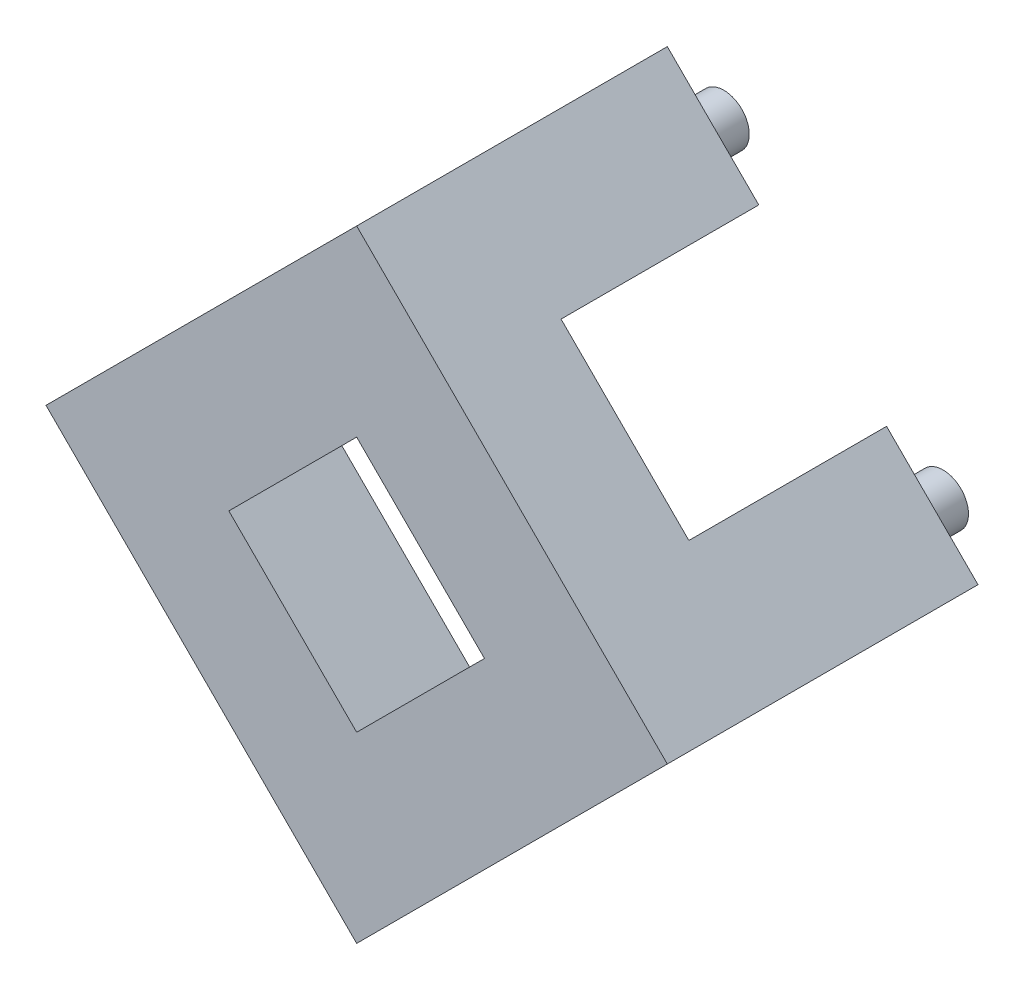
SolidWorks part; units mm, degrees
ref_plane "Plan de face" through (0, 0, 0) normal (0, 0, 1) x (1, 0, 0)
ref_plane "Plan de dessus" through (0, 0, 0) normal (0, 1, 0) x (1, 0, 0)
ref_plane "Plan de droite" through (0, 0, 0) normal (1, 0, 0) x (0, 0, -1)
sketch "Esquisse1" plane through (0, 0, 15) normal (0, 0, 1) x (1, 0, 0)
  line L0 (0, 55) -> (-16.1863, 38.8137)
  line L1 (32.3726, 55) -> (-32.3726, 55) construction
  line L2 (0, 22.6274) -> (-115.8112, 138.4386) construction
  line L3 (-16.1863, 38.8137) -> (0, 22.6274)
  line L4 (0, 22.6274) -> (16.1863, 38.8137)
  line L5 (115.8112, 138.4386) -> (0, 22.6274) construction
  line L6 (16.1863, 38.8137) -> (0, 55)
  line L7 (-38.8137, 16.1863) -> (-55, 0)
  line L8 (-55, 0) -> (-38.8137, -16.1863)
  line L9 (-38.8137, -16.1863) -> (-22.6274, 0)
  line L10 (-22.6274, 0) -> (-38.8137, 16.1863)
  line L11 (-16.1863, -38.8137) -> (0, -55)
  line L12 (0, -55) -> (16.1863, -38.8137)
  line L13 (16.1863, -38.8137) -> (0, -22.6274)
  line L14 (0, -22.6274) -> (-16.1863, -38.8137)
  line L15 (38.8137, -16.1863) -> (55, 0)
  line L16 (55, 0) -> (38.8137, 16.1863)
  line L17 (38.8137, 16.1863) -> (22.6274, 0)
  line L18 (22.6274, 0) -> (38.8137, -16.1863)
  point P26 (0, 0)
  dimension "D1" = 4
extrude "Boss.-Extru.1" add sketch "Esquisse1" along normal blind 50 and the other way up to surface (5 mm away)
sketch "Esquisse3" plane through (0, 0, 65) normal (0, 0, 1) x (1, 0, 0)
  line L0 (16.1863, 38.8137) -> (38.8137, 16.1863)
  line L1 (38.8137, 16.1863) -> (22.6274, 0)
  line L2 (22.6274, 0) -> (0, 22.6274)
  line L3 (0, 22.6274) -> (16.1863, 38.8137)
  line L4 (0, 22.6274) -> (-22.6274, 0)
  line L5 (-22.6274, 0) -> (-38.8137, 16.1863)
  line L6 (-38.8137, 16.1863) -> (-16.1863, 38.8137)
  line L7 (-16.1863, 38.8137) -> (0, 22.6274)
  line L8 (-22.6274, 0) -> (0, -22.6274)
  line L9 (0, -22.6274) -> (-16.1863, -38.8137)
  line L10 (-16.1863, -38.8137) -> (-38.8137, -16.1863)
  line L11 (-55, 0) -> (-38.8137, -16.1863) construction
  line L12 (-22.6274, 0) -> (-138.4386, -115.8112) construction
  line L13 (-38.8137, -16.1863) -> (-22.6274, 0)
  line L14 (0, -22.6274) -> (22.6274, 0)
  line L15 (38.8137, -16.1863) -> (16.1863, -38.8137)
  line L16 (16.1863, -38.8137) -> (0, -22.6274)
  line L17 (38.8137, -16.1863) -> (22.6274, 0)
  line M3 (-16.1863, 38.8137) -> (0, 22.6274)
  line M4 (0, 22.6274) -> (16.1863, 38.8137)
extrude "Boss.-Extru.2" add sketch "Esquisse3" against normal blind 20 contours L2 L1 L0 M4 | L6 L5 L4 M3 | L15 L17 L14 L16 | L13 L10 L9 L8
sketch "Esquisse4" plane through (0, 0, 10) normal (0, 0, -1) x (-1, 0, 0)
  circle A0 centre (-38.8137, 0) radius 5 construction
  circle A1 centre (0, -38.8137) radius 5 construction
  circle A2 centre (0, 38.8137) radius 5 construction
  circle A3 centre (38.8137, 0) radius 5 construction
  circle A8 centre (-38.8137, 0) radius 5
  circle A9 centre (0, -38.8137) radius 5
  circle A10 centre (0, 38.8137) radius 5
  circle A11 centre (38.8137, 0) radius 5
  circle A12 centre (38.8137, 0) radius 4.5
  circle A13 centre (0, -38.8137) radius 4.5
  circle A14 centre (-38.8137, 0) radius 4.5
  circle A15 centre (0, 38.8137) radius 4.5
  dimension "D1" = 0.5
extrude "Boss.-Extru.3" add sketch "Esquisse4" along normal up to surface (10 mm away) contours A13 | A14 | A15 | A12
